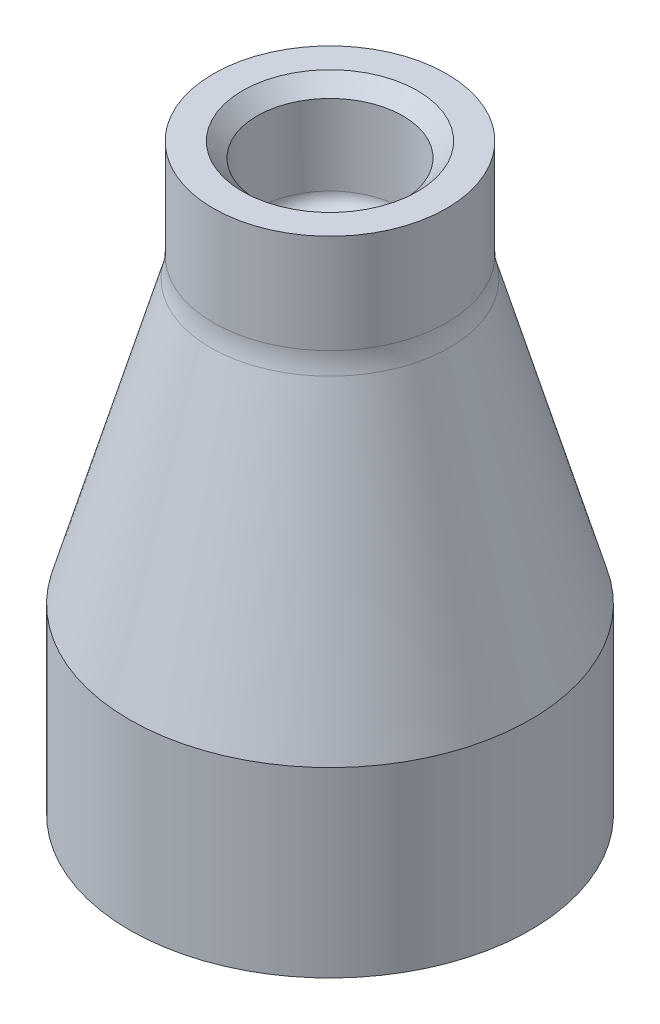
SolidWorks part; units mm, degrees
ref_plane "前视基准面" through (0, 0, 0) normal (0, 0, 1) x (1, 0, 0)
ref_plane "上视基准面" through (0, 0, 0) normal (0, 1, 0) x (1, 0, 0)
ref_plane "右视基准面" through (0, 0, 0) normal (1, 0, 0) x (0, 0, -1)
other "Configuration Table"
sketch "草图1" plane through (0, 0, 0) normal (0, 0, 1) x (1, 0, 0)
  line L0 (0, 36.444) -> (0, -34.3863) construction
  line L1 (0, 0) -> (16, 0)
  line L2 (16, 0) -> (16, -15)
  line L3 (16, -15) -> (27.5, -55)
  line L4 (27.5, -55) -> (27.5, -80)
  line L5 (27.5, -80) -> (0, -80)
  line L6 (0, -80) -> (0, 0)
  point P5 (54.1858, -55)
  dimension "D1" = 15
  dimension "D2" = 80
  dimension "D3" = 25
  dimension "D4" = 16
  dimension "D5" = 27.5
revolve "旋转1" add sketch "草图1" angle 360 about L0
sketch "草图2" plane through (0, 0, 0) normal (0, 1, 0) x (1, 0, 0)
  circle A0 centre (0, 0) radius 10
  dimension "D1" = 20
extrude "切除-拉伸1" cut sketch "草图2" against normal blind 15
chamfer "倒角1" distance 2 angle 45 1 edges at (0, 0, 10)
fillet "圆角1" radius 2 1 edges at (0, -15, 10)
fillet "圆角2" radius 10 1 edges at (0, -15, 16)
